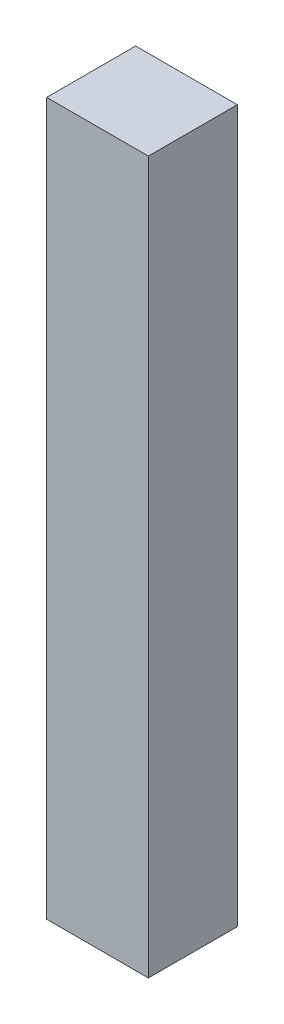
SolidWorks part; units mm, degrees
material "6063-O"
ref_plane "Front Plane" through (0, 0, 0) normal (0, 0, 1) x (1, 0, 0)
ref_plane "Top Plane" through (0, 0, 0) normal (0, 1, 0) x (1, 0, 0)
ref_plane "Right Plane" through (0, 0, 0) normal (1, 0, 0) x (0, 0, -1)
sketch "Sketch1" plane through (0, 0, 0) normal (0, 1, 0) x (1, 0, 0)
  line L1 (-4, 3.5) -> (4, 3.5)
  line L2 (-4, 3.5) -> (-4, -3.5)
  line L3 (-4, -3.5) -> (4, -3.5)
  line L4 (4, 3.5) -> (4, -3.5)
  line L5 (0, -3.5) -> (0, 3.5) construction
  line L6 (-4, 0) -> (4, 0) construction
  point P0 (0, 0)
  dimension "D1" = 7
  dimension "D2" = 8
extrude "Boss-Extrude1" add sketch "Sketch1" along normal mid plane 56
